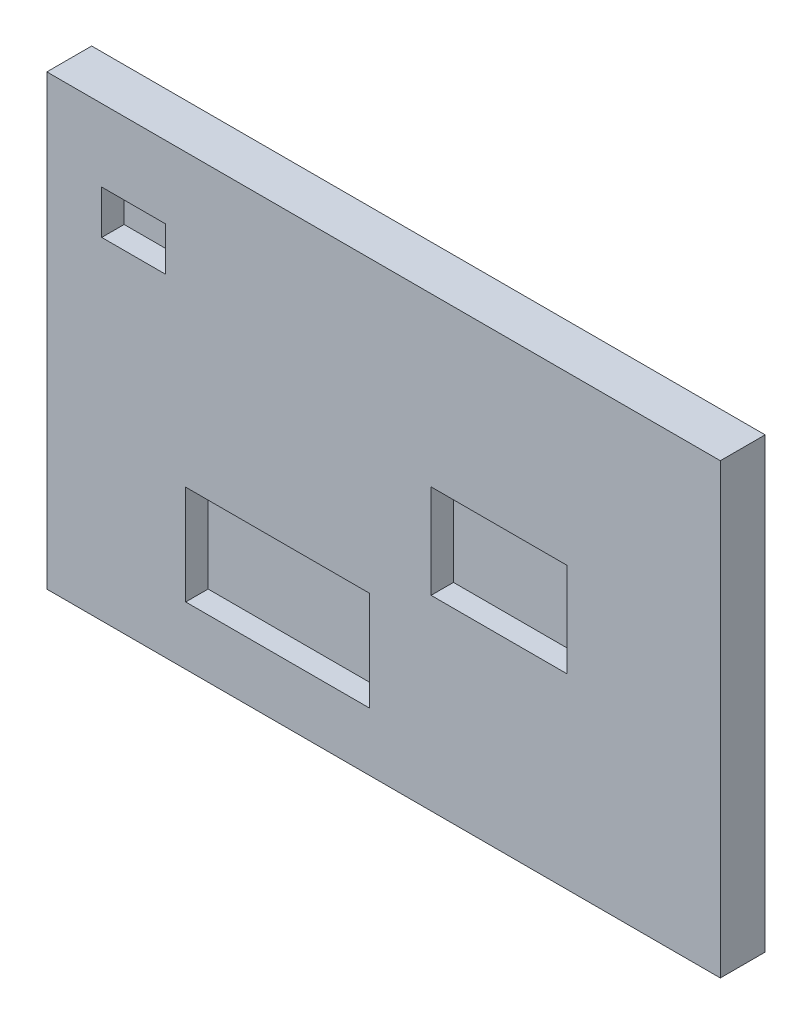
SolidWorks part; units mm, degrees
ref_plane "Front Plane" through (0, 0, 0) normal (0, 0, 1) x (1, 0, 0)
ref_plane "Top Plane" through (0, 0, 0) normal (0, 1, 0) x (1, 0, 0)
ref_plane "Right Plane" through (0, 0, 0) normal (1, 0, 0) x (0, 0, -1)
sketch "Sketch1" plane through (0, 0, 0) normal (0, 0, 1) x (1, 0, 0)
  line L1 (-44.7236, 25.8794) -> (105.608, 25.8794)
  line L2 (-44.7236, 25.8794) -> (-44.7236, -74.1206)
  line L3 (-44.7236, -74.1206) -> (105.608, -74.1206)
  line L4 (105.608, 25.8794) -> (105.608, -74.1206)
  dimension "D1" = 100
  dimension "D2" = 150.3317
extrude "Boss-Extrude1" add sketch "Sketch1" along normal blind 10
sketch "Sketch2" plane through (0, 0, 10) normal (0, 0, 1) x (1, 0, 0)
  line L1 (-32.4734, 9.7356) -> (-18.1946, 9.7356)
  line L2 (-32.4734, 9.7356) -> (-32.4734, 0)
  line L3 (-32.4734, 0) -> (-18.1946, 0)
  line L4 (-18.1946, 9.7356) -> (-18.1946, 0)
  line L5 (41.0397, -11.4594) -> (71.3819, -11.4594)
  line L6 (41.0397, -11.4594) -> (41.0397, -32.4313)
  line L7 (41.0397, -32.4313) -> (71.3819, -32.4313)
  line L8 (71.3819, -11.4594) -> (71.3819, -32.4313)
  line L9 (-13.7325, -38.9013) -> (27.3187, -38.9013)
  line L10 (-13.7325, -38.9013) -> (-13.7325, -61.1002)
  line L11 (-13.7325, -61.1002) -> (27.3187, -61.1002)
  line L12 (27.3187, -38.9013) -> (27.3187, -61.1002)
extrude "Cut-Extrude1" cut sketch "Sketch2" against normal blind 5
